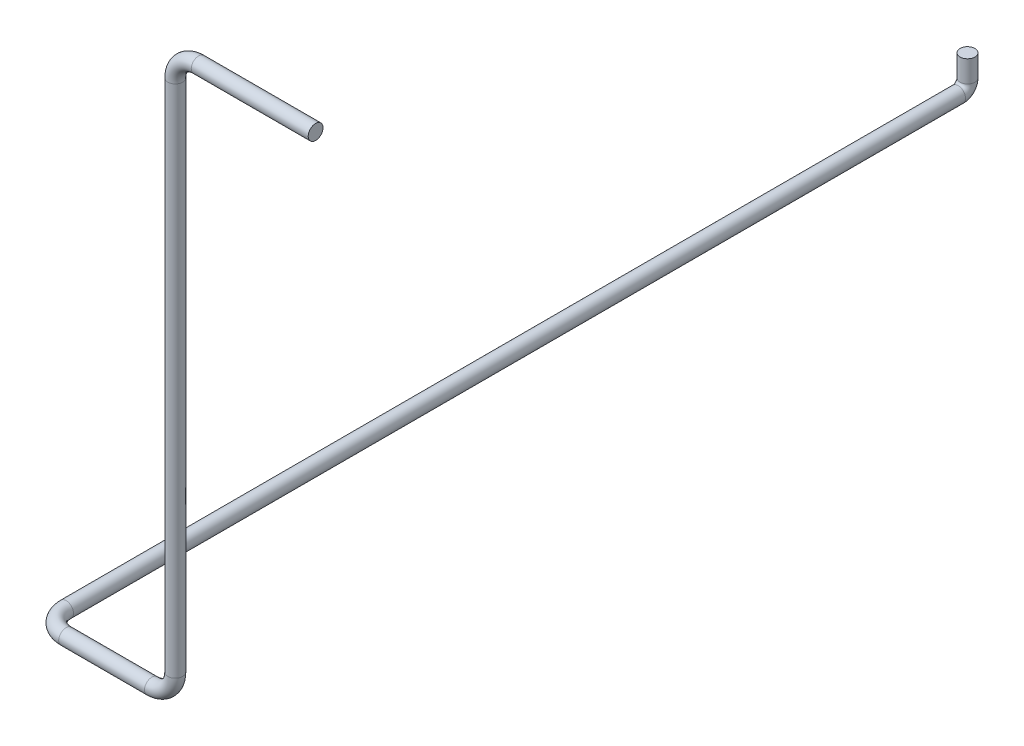
SolidWorks part; units mm, degrees
ref_plane "Alzado" through (0, 0, 0) normal (0, 0, 1) x (1, 0, 0)
ref_plane "Planta" through (0, 0, 0) normal (0, 1, 0) x (1, 0, 0)
ref_plane "Vista lateral" through (0, 0, 0) normal (1, 0, 0) x (0, 0, -1)
sketch "Croquis1" plane through (0, 0, 0) normal (0, 1, 0) x (1, 0, 0)
  circle A0 centre (0, 0) radius 9.525
  dimension "D1" = 19.05
extrude "Saliente-Extruir1" add sketch "Croquis1" against normal blind 10
sketch3d "Croquis3D1"
  line L0 (0, -10, 0) -> (0, -28, 0)
  line L1 (0, -10, 0) -> (0, 0, 0) construction
  line L2 (0, -40, 12) -> (0, -40, 1156)
  line L3 (30, -40, 1186) -> (140, -40, 1186)
  line L4 (170, -10, 1186) -> (170, 650, 1186)
  line L5 (200, 680, 1186) -> (350, 680, 1186)
  arc A0 (170, 650, 1186) -> (200, 680, 1186) centre (200, 650, 1186) ccw
  arc A1 (140, -40, 1186) -> (170, -10, 1186) centre (140, -10, 1186) ccw
  arc A2 (0, -40, 1156) -> (30, -40, 1186) centre (30, -40, 1156) ccw
  arc A3 (0, -28, 0) -> (0, -40, 12) centre (0, -28, 12) ccw
  point P10 (170, 680, 1186)
  point P11 (200, 650, 1156)
  point P14 (170, -40, 1186)
  point P15 (140, -10, 1216)
  point P18 (0, -40, 1186)
  point P19 (30, -10, 1156)
  point P22 (0, -40, 0)
  point P23 (-12, -28, 12)
  dimension "D6" = 30
  dimension "D7" = 12
  dimension "D1" = 30
  dimension "D2" = 1186
  dimension "D3" = 170
  dimension "D5" = 180
  dimension "D4" = 720
sketch "Croquis2" plane through (0, -10, 0) normal (0, -1, 0) x (1, 0, 0)
  circle A0 centre (0, 0) radius 9.525
sweep "Barrer1" add profiles "Croquis2" path "Croquis3D1"
